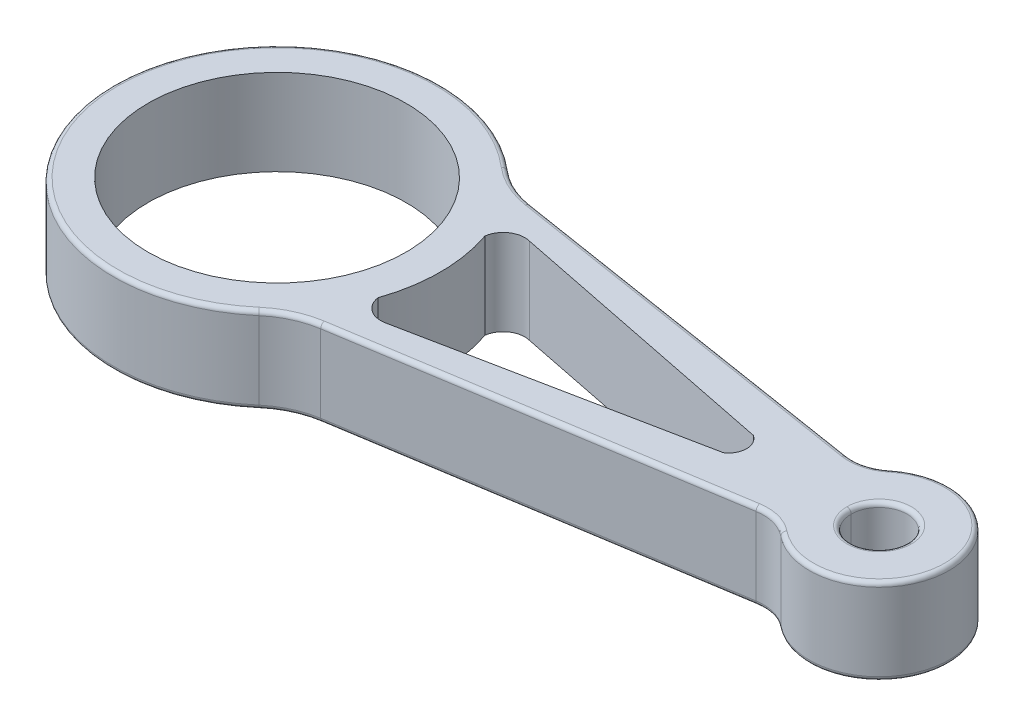
SolidWorks part; units mm, degrees
material "Plain Carbon Steel"
ref_plane "Front Plane" through (0, 0, 0) normal (0, 0, 1) x (1, 0, 0)
ref_plane "Top Plane" through (0, 0, 0) normal (0, 1, 0) x (1, 0, 0)
ref_plane "Right Plane" through (0, 0, 0) normal (1, 0, 0) x (0, 0, -1)
sketch "Sketch1" plane through (0, 0, 0) normal (0, 1, 0) x (1, 0, 0)
  line L0 (-17.7498, 0) -> (152.8452, 0) construction
  line L3 (28.3093, -25.3492) -> (126.9794, -9.7224)
  line L5 (28.3093, 25.3492) -> (126.9794, 9.7224)
  circle A0 centre (0, 0) radius 30
  circle A1 centre (140, 0) radius 6.5
  arc A4 (126.9794, -9.7224) -> (126.9794, 9.7224) centre (140, 0) ccw
  arc A5 (28.3093, 25.3492) -> (28.3093, -25.3492) centre (0, 0) ccw
  dimension "D1" = 60
  dimension "D3" = 32.5
  dimension "D4" = 13
  dimension "D5" = 76
  dimension "D2" = 140
extrude "Boss-Extrude1" add sketch "Sketch1" along normal mid plane 20
fillet "Fillet1" radius 20 2 edges at (28.3093, 0, -25.3492) (28.3093, 0, 25.3492)
fillet "Fillet2" radius 10 2 edges at (126.9794, 0, -9.7224) (126.9794, 0, 9.7224)
sketch "Sketch2" plane through (0, -10, 0) normal (0, -1, 0) x (1, 0, 0)
  line L0 (0, 0) -> (140, 0) construction
  line L6 (42.0846, -16.5865) -> (107.2586, -3.4931)
  line L7 (42.0846, 16.5865) -> (107.2586, 3.4931)
  arc A0 (35.903, -12.449) -> (35.903, 12.449) centre (0, 0) ccw
  arc A1 (24.667, 28.9057) -> (24.667, -28.9057) centre (0, 0) ccw construction
  arc A2 (35.903, 12.449) -> (42.0846, 16.5865) centre (40.8525, 11.7407) cw
  arc A3 (35.903, -12.449) -> (42.0846, -16.5865) centre (40.8525, -11.7407) ccw
  circle A4 centre (140, 0) radius 6.5 construction
  arc A5 (107.2586, -3.4931) -> (107.2586, 3.4931) centre (105, 0) ccw
  dimension "D1" = 5
  dimension "D4" = 35
extrude "Cut-Extrude1" cut sketch "Sketch2" against normal through all
split line "Split Line1"
fillet "Fillet3" radius 1 20 edges at (140, 10, -6.5) (140, 10, 6.5) (140, -10, -6.5) (140, -10, 6.5) (126.0695, -10, 10.7417) (78.2192, -10, 17.4448) (29.2803, -10, 25.9545) (-38, -10, 0) (29.2803, -10, -25.9545) (78.2192, -10, -17.4448) (126.0695, -10, -10.7417) (126.0695, 10, 10.7417) (78.2192, 10, 17.4448) (29.2803, 10, 25.9545) (-38, 10, 0) (29.2803, 10, -25.9545) (78.2192, 10, -17.4448) (126.0695, 10, -10.7417) (156.25, -10, 0) (156.25, 10, 0)
